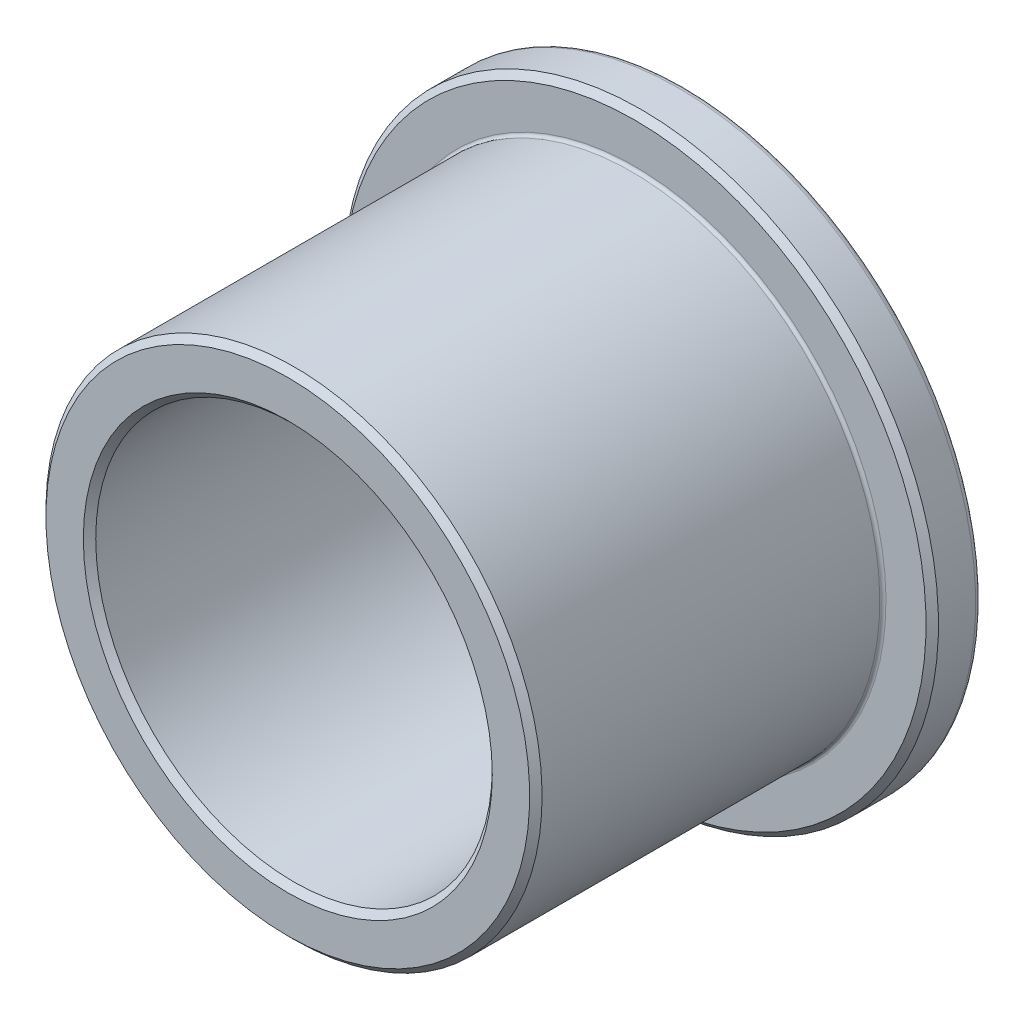
SolidWorks part; units mm, degrees
ref_plane "Front Plane" through (0, 0, 0) normal (0, 0, 1) x (1, 0, 0)
ref_plane "Top Plane" through (0, 0, 0) normal (0, 1, 0) x (1, 0, 0)
ref_plane "Right Plane" through (0, 0, 0) normal (1, 0, 0) x (0, 0, -1)
sketch "Sketch1" plane through (0, 0, 0) normal (0, 0, 1) x (1, 0, 0)
  circle A0 centre (0, 0) radius 12.7
  circle A1 centre (0, 0) radius 15.8877
  circle A2 centre (0, 0) radius 19.05
  point P5 (0, 15.8877)
  point P6 (0, 12.7)
  point P7 (0, 19.05)
  dimension "ID" = 25.4
  dimension "OD" = 31.7754
  dimension "Flange OD" = 38.1
sketch "Sketch2" plane through (0, 0, 0) normal (1, 0, 0) x (0, 0, -1)
  line L0 (12.7, 0) -> (-12.7, 0)
  line L1 (12.7, 0) -> (12.7, 19.05)
  line L2 (12.7, 19.05) -> (9.525, 19.05)
  line L3 (9.525, 19.05) -> (9.525, 15.8877)
  line L4 (9.525, 15.8877) -> (-12.7, 15.8877)
  line L5 (-12.7, 15.8877) -> (-12.7, 12.7)
  line L6 (-12.7, 12.7) -> (12.7, 12.7)
  point P4 (0, 0)
  dimension "Flange Thickness" = 3.175
  dimension "Length" = 25.4
sketch "Sketch3" plane through (0, 0, 0) normal (1, 0, 0) x (0, 0, -1)
  line L0 (12.7, 19.05) -> (9.525, 19.05) construction
  line L1 (9.525, 19.05) -> (9.525, 15.8877) construction
  line L2 (9.525, 15.8877) -> (-12.7, 15.8877) construction
  line L3 (-12.7, 12.7) -> (12.7, 12.7) construction
  line L4 (-12.7, 15.8877) -> (-12.7, 12.7) construction
  line L5 (12.7, 19.05) -> (9.525, 19.05)
  line L6 (9.525, 19.05) -> (9.525, 15.8877)
  line L7 (9.525, 15.8877) -> (-12.7, 15.8877)
  line L8 (-12.7, 12.7) -> (12.7, 12.7)
  line L9 (-12.7, 15.8877) -> (-12.7, 12.7)
  line L10 (12.7, 19.05) -> (12.7, 12.7)
revolve "Revolve1" add sketch "Sketch3" angle 360 about L0
chamfer "Chamfer1" distance 0.3969 angle 45 3 edges at (0, 19.05, -9.525) (0, 15.8877, 12.7) (0, 12.7, 12.7)
fillet "Fillet1" radius 0.3969 1 edges at (0, 19.05, -12.7)
fillet "Fillet2" radius 0.1984 1 edges at (0, 15.8877, -9.525)
equation "\"D1@Chamfer1\"=\"Flange Thickness@Sketch2\"*.125"
equation "\"D1@Fillet1\"=\"D1@Chamfer1\""
equation "\"D1@Fillet2\"=\"D1@Fillet1\"*.5"
